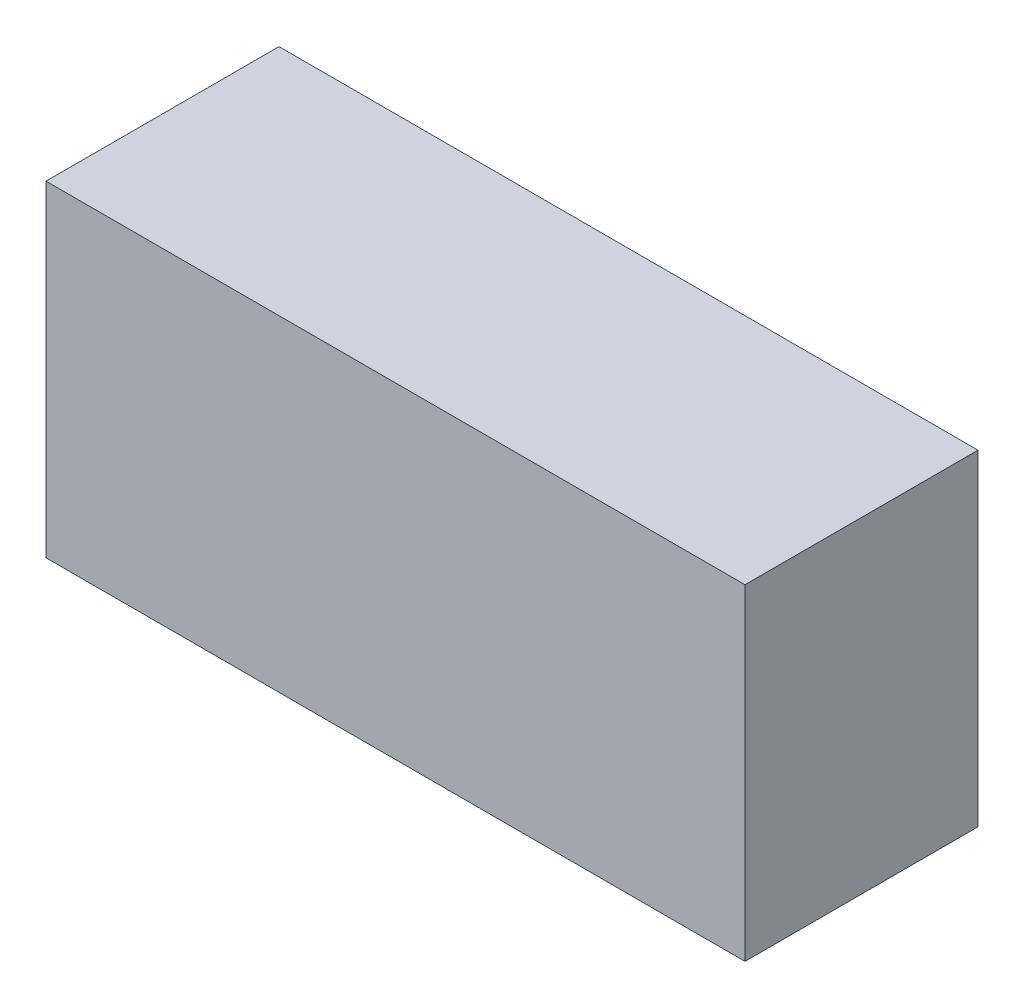
SolidWorks part; units mm, degrees
ref_plane "Front Plane" through (0, 0, 0) normal (0, 0, 1) x (1, 0, 0)
ref_plane "Top Plane" through (0, 0, 0) normal (0, 1, 0) x (1, 0, 0)
ref_plane "Right Plane" through (0, 0, 0) normal (1, 0, 0) x (0, 0, -1)
sketch "Sketch1" plane through (0, 3, 0) normal (0, 1, 0) x (1, 0, 0)
  line L0 (-37.5, -12.5) -> (37.5, -12.5) construction
  line L1 (37.5, -12.5) -> (37.5, -37.5) construction
  line L2 (-37.5, -37.5) -> (37.5, -37.5) construction
  line L3 (-37.5, -12.5) -> (-37.5, -37.5) construction
  line L4 (-37.5, -12.5) -> (37.5, -12.5)
  line L5 (37.5, -12.5) -> (37.5, -37.5)
  line L6 (-37.5, -37.5) -> (37.5, -37.5)
  line L7 (-37.5, -12.5) -> (-37.5, -37.5)
extrude "Boss-Extrude1" add sketch "Sketch1" along normal blind 35
